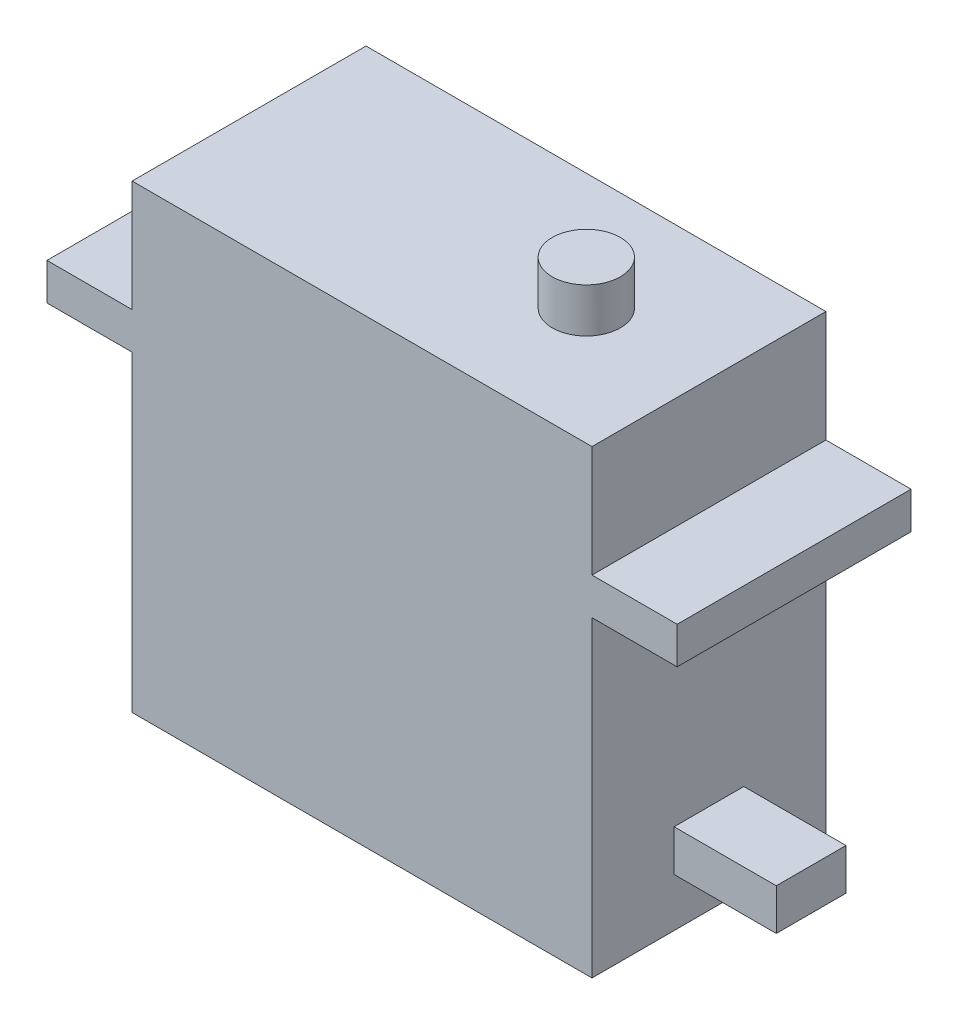
SolidWorks part; units mm, degrees
ref_plane "Front Plane" through (0, 0, 0) normal (0, 0, 1) x (1, 0, 0)
ref_plane "Top Plane" through (0, 0, 0) normal (0, 1, 0) x (1, 0, 0)
ref_plane "Right Plane" through (0, 0, 0) normal (1, 0, 0) x (0, 0, -1)
sketch "Sketch1" plane through (0, 0, 0) normal (0, 0, 1) x (1, 0, 0)
  line L1 (-20.25, -20.265) -> (20.25, -20.265)
  line L2 (-20.25, -20.265) -> (-20.25, 20.265)
  line L3 (-20.25, 20.265) -> (20.25, 20.265)
  line L4 (20.25, -20.265) -> (20.25, 20.265)
  line L5 (-20.25, -20.265) -> (20.25, 20.265) construction
  line L6 (-20.25, 20.265) -> (20.25, -20.265) construction
  point P0 (0, 0)
  dimension "D1" = 40.53
  dimension "D2" = 40.5
extrude "Boss-Extrude1" add sketch "Sketch1" along normal blind 20.6
sketch "Sketch2" plane through (0, 20.265, 0) normal (0, 1, 0) x (1, 0, 0)
  line L0 (-20.25, -20.6) -> (-20.25, 0) construction
  line L1 (-20.25, -20.6) -> (-27.75, -20.6)
  line L2 (-20.25, -20.6) -> (-20.25, 0)
  line L3 (-20.25, 0) -> (-27.75, 0)
  line L4 (-27.75, -20.6) -> (-27.75, 0)
  line L5 (20.25, 0) -> (-20.25, 0) construction
  line L6 (20.25, -20.6) -> (27.75, -20.6)
  line L7 (20.25, -20.6) -> (20.25, 0)
  line L8 (20.25, 0) -> (27.75, 0)
  line L9 (27.75, -20.6) -> (27.75, 0)
  line L10 (20.25, -20.6) -> (20.25, 0) construction
  point P5 (20.25, 0)
  dimension "D1" = 7.5
  dimension "D2" = 7.5
extrude "Boss-Extrude2" add sketch "Sketch2" against normal blind 3.25 from offset 9.8 offset against normal yes
sketch "Sketch3" plane through (0, 20.265, 0) normal (0, 1, 0) x (1, 0, 0)
  line L0 (-20.25, -10.3) -> (9.45, -10.3) construction
  line L1 (-20.25, -20.6) -> (-20.25, 0) construction
  circle A1 centre (9.45, -10.3) radius 3
  dimension "29.7" = 29.7
extrude "Boss-Extrude3" add sketch "Sketch3" along normal blind 3.9
sketch "Sketch4" plane through (20.25, 0, 0) normal (1, 0, 0) x (0, 0, -1)
  line L0 (-10.3, 20.265) -> (-10.3, -14.165) construction
  line L1 (-20.6, 20.265) -> (0, 20.265) construction
  line L2 (-20.6, -20.265) -> (0, -20.265) construction
  line L3 (-13.37, -15.985) -> (-7.23, -15.985)
  line L4 (-13.37, -15.985) -> (-13.37, -12.345)
  line L5 (-13.37, -12.345) -> (-7.23, -12.345)
  line L6 (-7.23, -15.985) -> (-7.23, -12.345)
  line L7 (-13.37, -15.985) -> (-7.23, -12.345) construction
  line L8 (-13.37, -12.345) -> (-7.23, -15.985) construction
  point P10 (-10.3, -20.265)
  dimension "D1" = 6.14
  dimension "D2" = 3.64
  dimension "D3" = 4.28
extrude "Boss-Extrude4" add sketch "Sketch4" along normal blind 9
